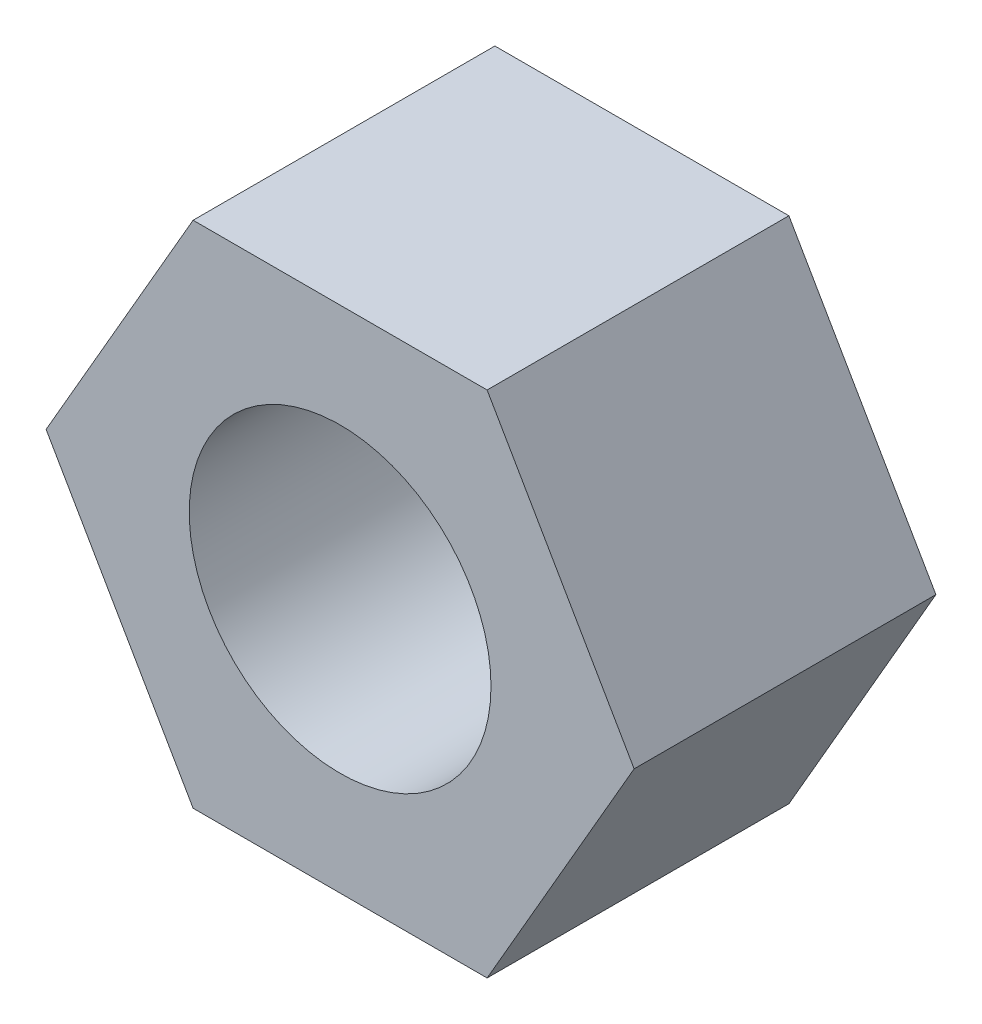
SolidWorks part; units mm, degrees
material "Chrome Stainless Steel"
ref_plane "Front Plane" through (0, 0, 0) normal (0, 0, 1) x (1, 0, 0)
ref_plane "Top Plane" through (0, 0, 0) normal (0, 1, 0) x (1, 0, 0)
ref_plane "Right Plane" through (0, 0, 0) normal (1, 0, 0) x (0, 0, -1)
sketch "Sketch1" plane through (0, 0, 0) normal (0, 0, 1) x (1, 0, 0)
  line L1 (7.7942, 0) -> (3.8971, 6.75)
  line L2 (3.8971, 6.75) -> (-3.8971, 6.75)
  line L3 (-3.8971, 6.75) -> (-7.7942, 0)
  line L4 (-7.7942, 0) -> (-3.8971, -6.75)
  line L5 (-3.8971, -6.75) -> (3.8971, -6.75)
  line L6 (3.8971, -6.75) -> (7.7942, 0)
  circle A0 centre (0, 0) radius 6.75 construction
  circle A1 centre (0, 0) radius 4
  dimension "D2" = 8
  dimension "D1" = 13.5
extrude "Boss-Extrude1" add sketch "Sketch1" along normal blind 8
